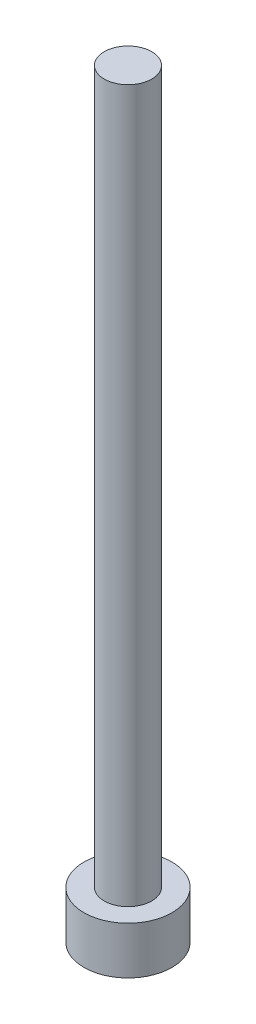
SolidWorks part; units mm, degrees
ref_plane "Front Plane" through (0, 0, 0) normal (0, 0, 1) x (1, 0, 0)
ref_plane "Top Plane" through (0, 0, 0) normal (0, 1, 0) x (1, 0, 0)
ref_plane "Right Plane" through (0, 0, 0) normal (1, 0, 0) x (0, 0, -1)
sketch "Sketch1" plane through (0, 0, 0) normal (0, 1, 0) x (1, 0, 0)
  circle A0 centre (0, 0) radius 2.78
  dimension "D1" = 5.56
extrude "Boss-Extrude1" add sketch "Sketch1" along normal blind 3
sketch "Sketch2" plane through (0, 3, 0) normal (0, 1, 0) x (1, 0, 0)
  circle A0 centre (0, 0) radius 1.5
  dimension "D1" = 3
extrude "Boss-Extrude2" add sketch "Sketch2" along normal blind 45
